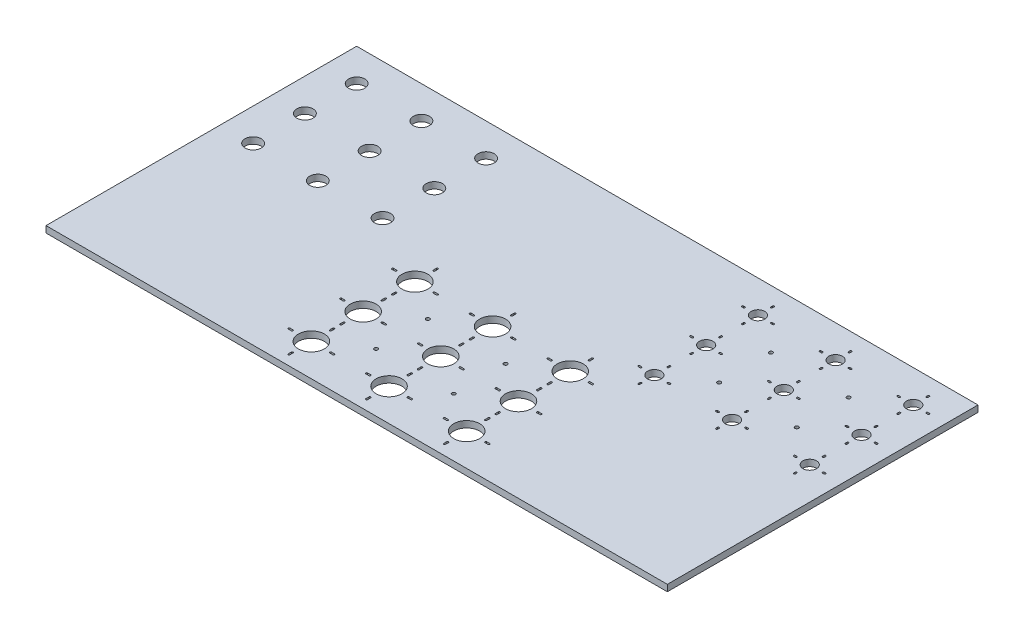
SolidWorks part; units mm, degrees
ref_plane "Front Plane" through (0, 0, 0) normal (0, 0, 1) x (1, 0, 0)
ref_plane "Top Plane" through (0, 0, 0) normal (0, 1, 0) x (1, 0, 0)
ref_plane "Right Plane" through (0, 0, 0) normal (1, 0, 0) x (0, 0, -1)
sketch "Sketch1" plane through (0, 0, 0) normal (0, 1, 0) x (1, 0, 0)
  line L1 (0, 0) -> (609.6, 0)
  line L2 (0, 0) -> (0, -304.8)
  line L3 (0, -304.8) -> (609.6, -304.8)
  line L4 (609.6, 0) -> (609.6, -304.8)
  dimension "D1" = 609.6
  dimension "D2" = 304.8
extrude "Boss-Extrude1" add sketch "Sketch1" along normal blind 6.35
sketch "Sketch2" plane through (0, 6.35, 0) normal (0, 1, 0) x (1, 0, 0)
  line L0 (0, 0) -> (0, -304.8) construction
  line L1 (609.6, 0) -> (0, 0) construction
  circle A0 centre (31.75, -31.75) radius 7.9375
  circle A1 centre (95.25, -31.75) radius 7.9375
  circle A2 centre (158.75, -31.75) radius 7.9375
  circle A3 centre (95.25, -82.55) radius 7.9375
  circle A4 centre (158.75, -82.55) radius 7.9375
  circle A5 centre (95.25, -133.35) radius 7.9375
  circle A6 centre (158.75, -133.35) radius 7.9375
  circle A7 centre (31.75, -82.55) radius 7.9375
  circle A8 centre (31.75, -133.35) radius 7.9375
  dimension "D1" = 15.875
  dimension "D6" = 63.5
  dimension "D7" = 50.8
  dimension "D2" = 31.75
  dimension "D3" = 31.75
  dimension "D4" = 3
  dimension "D5" = 3
extrude "Cut-Extrude1" cut sketch "Sketch2" against normal blind 6.35
sketch "Sketch3" plane through (0, 6.35, 0) normal (0, 1, 0) x (1, 0, 0)
  line L0 (609.6, 0) -> (0, 0) construction
  line L1 (609.6, -304.8) -> (609.6, 0) construction
  circle A0 centre (577.85, -31.75) radius 6.6675
  circle A1 centre (501.65, -31.75) radius 6.6675
  circle A2 centre (425.45, -31.75) radius 6.6675
  circle A3 centre (501.65, -82.55) radius 6.6675
  circle A4 centre (425.45, -82.55) radius 6.6675
  circle A5 centre (501.65, -133.35) radius 6.6675
  circle A6 centre (425.45, -133.35) radius 6.6675
  circle A7 centre (577.85, -82.55) radius 6.6675
  circle A8 centre (577.85, -133.35) radius 6.6675
  dimension "D1" = 13.335
  dimension "D6" = 76.2
  dimension "D2" = 31.75
  dimension "D3" = 31.75
  dimension "D7" = 50.8
  dimension "D4" = 3
  dimension "D5" = 3
extrude "Cut-Extrude2" cut sketch "Sketch3" against normal blind 6.35
sketch "Sketch4" plane through (0, 6.35, 0) normal (0, 1, 0) x (1, 0, 0)
  line L0 (304.8, 0) -> (304.8, -304.8) construction
  line L1 (609.6, 0) -> (0, 0) construction
  line L2 (0, -304.8) -> (609.6, -304.8) construction
  circle A0 centre (304.8, -273.05) radius 12.7
  circle A1 centre (228.6, -273.05) radius 12.7
  circle A2 centre (381, -273.05) radius 12.7
  circle A3 centre (228.6, -222.25) radius 12.7
  circle A4 centre (304.8, -222.25) radius 12.7
  circle A5 centre (381, -222.25) radius 12.7
  circle A6 centre (228.6, -171.45) radius 12.7
  circle A7 centre (304.8, -171.45) radius 12.7
  circle A8 centre (381, -171.45) radius 12.7
  dimension "D1" = 25.4
  dimension "D3" = 25.4
  dimension "D4" = 25.4
  dimension "D2" = 31.75
  dimension "D5" = 76.2
  dimension "D6" = 76.2
  dimension "D7" = 3
extrude "Cut-Extrude3" cut sketch "Sketch4" against normal through all
sketch "Sketch5" [suppressed] plane through (0, 6.35, 0) normal (0, 1, 0) x (1, 0, 0)
  line L0 (0, -151.13) -> (609.6, -151.13) construction
  line L2 (0, 0) -> (0, -304.8) construction
  line L3 (609.6, -304.8) -> (609.6, 0) construction
  line L4 (31.75, -133.35) -> (577.85, -133.35) construction
  line L5 (228.6, -171.45) -> (381, -171.45) construction
  line L6 (304.8, -171.45) -> (304.8, -151.13) construction
  line L7 (501.65, -133.35) -> (501.65, -151.13) construction
  line L8 (425.45, -31.75) -> (425.45, -133.35) construction
  line L9 (266.7, -154.305) -> (342.9, -154.305)
  line L10 (266.7, -154.305) -> (266.7, -147.955)
  line L11 (266.7, -147.955) -> (342.9, -147.955)
  line L12 (342.9, -154.305) -> (342.9, -147.955)
  line L13 (304.8, -147.955) -> (304.8, -154.305) construction
  line L14 (266.7, -151.13) -> (342.9, -151.13) construction
  line L15 (463.55, -147.955) -> (539.75, -147.955)
  line L16 (463.55, -147.955) -> (463.55, -154.305)
  line L17 (463.55, -154.305) -> (539.75, -154.305)
  line L18 (539.75, -147.955) -> (539.75, -154.305)
  line L19 (501.65, -154.305) -> (501.65, -147.955) construction
  line L20 (463.55, -151.13) -> (539.75, -151.13) construction
  line L21 (381, -171.45) -> (381, -273.05) construction
  line L22 (406.4, 0) -> (406.4, -304.8) construction
  line L23 (609.6, 0) -> (0, 0) construction
  line L24 (0, -304.8) -> (609.6, -304.8) construction
  line L25 (425.45, -82.55) -> (406.4, -82.55) construction
  line L26 (381, -222.25) -> (406.4, -222.25) construction
  line L27 (539.75, -17.145) -> (539.75, -10.795)
  line L28 (409.575, -44.45) -> (403.225, -44.45)
  line L29 (409.575, -44.45) -> (409.575, -120.65)
  line L30 (409.575, -120.65) -> (403.225, -120.65)
  line L31 (403.225, -44.45) -> (403.225, -120.65)
  line L32 (406.4, -120.65) -> (406.4, -44.45) construction
  line L33 (409.575, -82.55) -> (403.225, -82.55) construction
  line L34 (403.225, -260.35) -> (409.575, -260.35)
  line L35 (403.225, -260.35) -> (403.225, -184.15)
  line L36 (403.225, -184.15) -> (409.575, -184.15)
  line L37 (409.575, -260.35) -> (409.575, -184.15)
  line L38 (406.4, -184.15) -> (406.4, -260.35) construction
  line L39 (403.225, -222.25) -> (409.575, -222.25) construction
  line L40 (463.55, -10.795) -> (539.75, -10.795)
  line L41 (463.55, -17.145) -> (463.55, -10.795)
  line L42 (463.55, -17.145) -> (539.75, -17.145)
  line L43 (593.725, -120.65) -> (600.075, -120.65)
  line L44 (600.075, -44.45) -> (600.075, -120.65)
  line L45 (593.725, -44.45) -> (600.075, -44.45)
  line L46 (593.725, -44.45) -> (593.725, -120.65)
  line L47 (266.7, -296.545) -> (342.9, -296.545)
  line L48 (342.9, -290.195) -> (342.9, -296.545)
  line L49 (266.7, -290.195) -> (342.9, -290.195)
  line L50 (266.7, -290.195) -> (266.7, -296.545)
  line L51 (206.375, -184.15) -> (200.025, -184.15)
  line L52 (200.025, -260.35) -> (200.025, -184.15)
  line L53 (206.375, -260.35) -> (200.025, -260.35)
  line L54 (206.375, -260.35) -> (206.375, -184.15)
  dimension "D1" = 20.32
  dimension "D2" = 6.35
  dimension "D3" = 76.2
  dimension "D4" = 6.35
  dimension "D5" = 76.2
  dimension "D6" = 25.4
  dimension "D7" = 6.35
  dimension "D8" = 6.35
  dimension "D9" = 76.2
  dimension "D10" = 76.2
extrude "Cut-Extrude4" [suppressed] cut sketch "Sketch5" against normal through all
sketch "Sketch6" plane through (0, 6.35, 0) normal (0, 1, 0) x (1, 0, 0)
  line L0 (228.6, -148.336) -> (228.6, -158.75) construction
  line L1 (228.6, -149.606) -> (228.6, -152.654) construction
  line L2 (229.4509, -149.606) -> (229.4509, -152.654)
  line L3 (227.7491, -149.606) -> (227.7491, -152.654)
  line L4 (250.444, -170.5991) -> (247.396, -170.5991)
  line L5 (250.444, -172.3009) -> (247.396, -172.3009)
  line L6 (250.444, -171.45) -> (247.396, -171.45) construction
  line L7 (229.4509, -193.294) -> (229.4509, -190.246)
  line L8 (227.7491, -193.294) -> (227.7491, -190.246)
  line L9 (228.6, -193.294) -> (228.6, -190.246) construction
  line L10 (206.756, -172.3009) -> (209.804, -172.3009)
  line L11 (206.756, -170.5991) -> (209.804, -170.5991)
  line L12 (206.756, -171.45) -> (209.804, -171.45) construction
  arc A0 (230.124, -149.86) -> (227.076, -149.86) centre (228.6, -149.86) ccw construction
  circle A1 centre (228.6, -171.45) radius 12.7 construction
  arc A2 (229.4509, -149.606) -> (227.7491, -149.606) centre (228.6, -149.606) ccw
  arc A3 (227.7491, -152.654) -> (229.4509, -152.654) centre (228.6, -152.654) ccw
  arc A4 (250.444, -172.3009) -> (250.444, -170.5991) centre (250.444, -171.45) ccw
  arc A5 (247.396, -170.5991) -> (247.396, -172.3009) centre (247.396, -171.45) ccw
  arc A6 (227.7491, -193.294) -> (229.4509, -193.294) centre (228.6, -193.294) ccw
  arc A7 (229.4509, -190.246) -> (227.7491, -190.246) centre (228.6, -190.246) ccw
  arc A8 (206.756, -170.5991) -> (206.756, -172.3009) centre (206.756, -171.45) ccw
  arc A9 (209.804, -172.3009) -> (209.804, -170.5991) centre (209.804, -171.45) ccw
  point P10 (228.6, -151.13)
  point P20 (248.92, -171.45)
  point P27 (228.6, -191.77)
  point P34 (208.28, -171.45)
  dimension "D1" = 1.7018
  dimension "D2" = 3.048
  dimension "D3" = 1.27
  dimension "D4" = 4
extrude "Cut-Extrude5" cut sketch "Sketch6" against normal through all
pattern_linear "LPattern1" count 3 spacing 76.2 along (1, 0, 0) count 3 spacing 50.8 along (0, 0, 1) of "Cut-Extrude5"
sketch "Sketch7" plane through (0, 6.35, 0) normal (0, 1, 0) x (1, 0, 0)
  line L0 (425.45, -18.288) -> (425.45, -16.764) construction
  line L1 (424.5991, -18.288) -> (424.5991, -16.764)
  line L2 (426.3009, -18.288) -> (426.3009, -16.764)
  line L3 (609.6, 0) -> (0, 0) construction
  line L4 (438.912, -32.6009) -> (440.436, -32.6009)
  line L5 (438.912, -30.8991) -> (440.436, -30.8991)
  line L6 (438.912, -31.75) -> (440.436, -31.75) construction
  line L7 (424.5991, -45.212) -> (424.5991, -46.736)
  line L8 (426.3009, -45.212) -> (426.3009, -46.736)
  line L9 (425.45, -45.212) -> (425.45, -46.736) construction
  line L10 (411.988, -30.8991) -> (410.464, -30.8991)
  line L11 (411.988, -32.6009) -> (410.464, -32.6009)
  line L12 (411.988, -31.75) -> (410.464, -31.75) construction
  arc A0 (424.5991, -18.288) -> (426.3009, -18.288) centre (425.45, -18.288) ccw
  arc A1 (426.3009, -16.764) -> (424.5991, -16.764) centre (425.45, -16.764) ccw
  arc A2 (438.912, -30.8991) -> (438.912, -32.6009) centre (438.912, -31.75) ccw
  arc A3 (440.436, -32.6009) -> (440.436, -30.8991) centre (440.436, -31.75) ccw
  arc A4 (426.3009, -45.212) -> (424.5991, -45.212) centre (425.45, -45.212) ccw
  arc A5 (424.5991, -46.736) -> (426.3009, -46.736) centre (425.45, -46.736) ccw
  arc A6 (411.988, -32.6009) -> (411.988, -30.8991) centre (411.988, -31.75) ccw
  arc A7 (410.464, -30.8991) -> (410.464, -32.6009) centre (410.464, -31.75) ccw
  point P3 (425.45, -17.526)
  point P15 (439.674, -31.75)
  point P22 (425.45, -45.974)
  point P29 (411.226, -31.75)
  dimension "D1" = 1.7018
  dimension "D2" = 1.524
  dimension "D3" = 16.764
  dimension "D4" = 4
extrude "Cut-Extrude6" cut sketch "Sketch7" against normal through all
pattern_linear "LPattern2" count 3 spacing 76.2 along (1, 0, 0) count 3 spacing 50.8 along (0, 0, 1) of "Cut-Extrude6"
sketch "Sketch8" plane through (0, 6.35, 0) normal (0, 1, 0) x (1, 0, 0)
  line L0 (228.6, -184.15) -> (228.6, -209.55) construction
  line L1 (228.6, -196.85) -> (304.8, -196.85) construction
  line L2 (304.8, -184.15) -> (304.8, -209.55) construction
  line L3 (381, -184.15) -> (381, -209.55) construction
  line L4 (292.1, -222.25) -> (317.5, -222.25) construction
  circle A0 centre (228.6, -171.45) radius 12.7 construction
  circle A1 centre (228.6, -222.25) radius 12.7 construction
  circle A2 centre (304.8, -171.45) radius 12.7 construction
  circle A3 centre (304.8, -222.25) radius 12.7 construction
  circle A4 centre (381, -171.45) radius 12.7 construction
  circle A5 centre (381, -222.25) radius 12.7 construction
  circle A9 centre (266.7, -196.85) radius 1.778
  circle A10 centre (342.9, -196.85) radius 1.778
  circle A11 centre (342.9, -247.65) radius 1.778
  circle A12 centre (266.7, -247.65) radius 1.778
  dimension "D1" = 3.556
extrude "Cut-Extrude7" cut sketch "Sketch8" against normal blind 2.54
sketch "Sketch9" plane through (0, 6.35, 0) normal (0, 1, 0) x (1, 0, 0)
  line L0 (425.45, -38.4175) -> (425.45, -75.8825) construction
  line L1 (501.65, -38.4175) -> (501.65, -75.8825) construction
  line L2 (501.65, -57.15) -> (425.45, -57.15) construction
  line L3 (494.9825, -82.55) -> (508.3175, -82.55) construction
  circle A0 centre (425.45, -31.75) radius 6.6675 construction
  circle A1 centre (425.45, -82.55) radius 6.6675 construction
  circle A2 centre (501.65, -31.75) radius 6.6675 construction
  circle A3 centre (501.65, -82.55) radius 6.6675 construction
  circle A4 centre (463.55, -57.15) radius 1.778
  circle A5 centre (539.75, -57.15) radius 1.778
  circle A6 centre (539.75, -107.95) radius 1.778
  circle A7 centre (463.55, -107.95) radius 1.778
  dimension "D1" = 3.556
extrude "Cut-Extrude8" cut sketch "Sketch9" against normal through all
